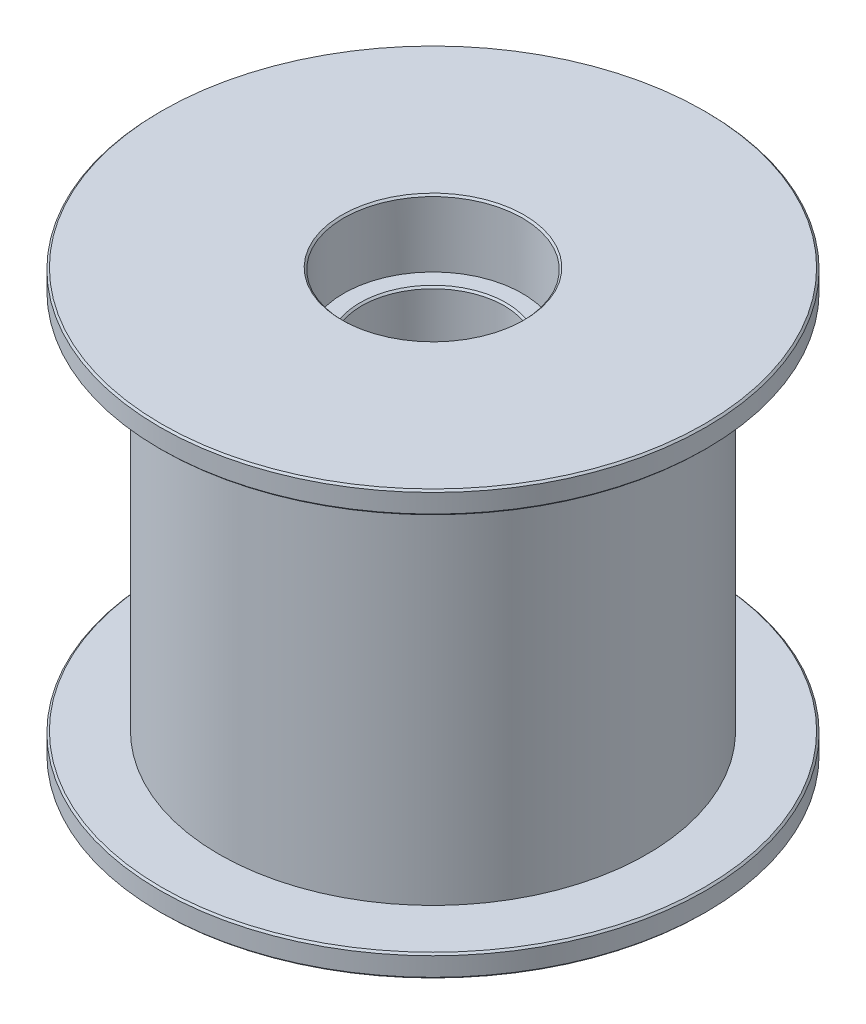
SolidWorks part; units mm, degrees
material "6061-T6 (SS)"
ref_plane "Front Plane" through (0, 0, 0) normal (0, 0, 1) x (1, 0, 0)
ref_plane "Top Plane" through (0, 0, 0) normal (0, 1, 0) x (1, 0, 0)
ref_plane "Right Plane" through (0, 0, 0) normal (1, 0, 0) x (0, 0, -1)
sketch "Sketch1" plane through (0, 0, 0) normal (0, 0, 1) x (1, 0, 0)
  line L0 (6.3627, 0) -> (19.4469, 0)
  line L1 (19.4469, 0) -> (19.4469, 1.5875)
  line L2 (19.4469, 1.5875) -> (15.24, 1.5875)
  line L3 (15.24, 1.5875) -> (15.24, 28.575)
  line L4 (15.24, 28.575) -> (19.4469, 28.575)
  line L5 (19.4469, 28.575) -> (19.4469, 30.1625)
  line L6 (19.4469, 30.1625) -> (6.3627, 30.1625)
  line L7 (0, 30.1625) -> (0, 0) construction
  line L8 (6.3627, 0) -> (6.3627, 4.7752)
  line L9 (6.3627, 4.7752) -> (5.08, 4.7752)
  line L10 (5.08, 4.7752) -> (5.08, 25.3873)
  line L11 (5.08, 25.3873) -> (6.3627, 25.3873)
  line L12 (6.3627, 25.3873) -> (6.3627, 30.1625)
  line L13 (6.3627, 30.1625) -> (0, 30.1625) construction
  line L14 (0, 0) -> (6.3627, 0) construction
  dimension "D1" = 30.48
  dimension "D2" = 38.8937
  dimension "D3" = 26.9875
  dimension "D4" = 30.1625
  dimension "D5" = 12.7254
  dimension "D6" = 4.7752
  dimension "D7" = 10.16
revolve "Revolve1" add sketch "Sketch1" angle 360 about L7
chamfer "Chamfer1" distance 0.127 angle 45 8 edges at (0, 28.575, 19.4469) (0, 1.5875, 19.4469) (0, 0, 6.3627) (0, 0, 19.4469) (0, 25.3873, 5.08) (0, 4.7752, 5.08) (0, 30.1625, 19.4469) (0, 30.1625, 6.3627)
